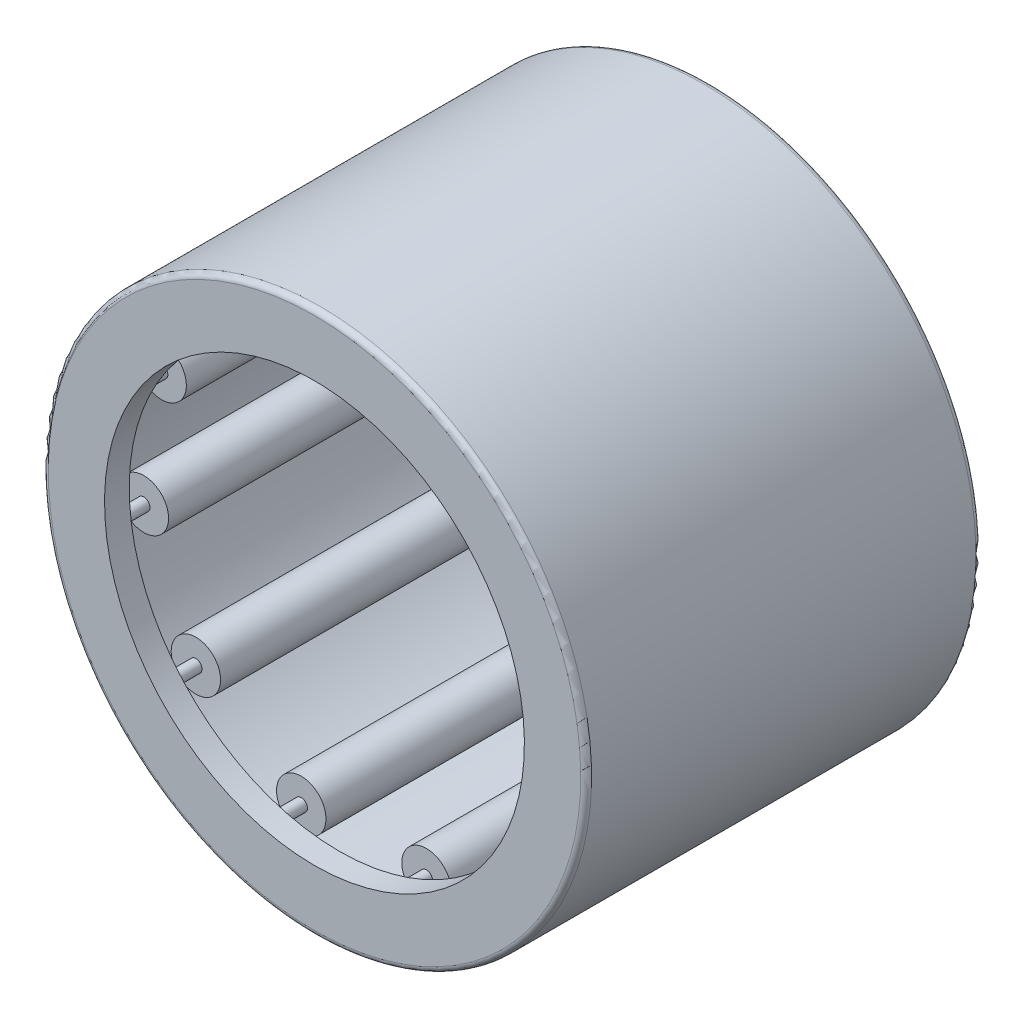
SolidWorks part; units mm, degrees
material "Plain Carbon Steel"
ref_plane "Front Plane" through (0, 0, 0) normal (0, 0, 1) x (1, 0, 0)
ref_plane "Top Plane" through (0, 0, 0) normal (0, 1, 0) x (1, 0, 0)
ref_plane "Right Plane" through (0, 0, 0) normal (1, 0, 0) x (0, 0, -1)
sketch "Sketch1" plane through (0, 0, 0) normal (1, 0, 0) x (0, 0, -1)
  line L0 (-6.35, 0) -> (6.35, 0) construction
  line L1 (0, 0) -> (0, 8.7313) construction
  line L2 (-6.35, 0) -> (-6.35, 8.7312) construction
  line L3 (-6.35, 8.7312) -> (6.35, 8.7312)
  line L4 (6.35, 8.7312) -> (6.35, 0) construction
  line L5 (6.35, 0) -> (5.5563, 0) construction
  line L6 (5.5563, 0) -> (5.5562, 7.9375) construction
  line L7 (5.5562, 7.9375) -> (-5.5562, 7.9375)
  line L8 (-5.5562, 7.9375) -> (-5.5563, 0) construction
  line L9 (-5.5563, 0) -> (-6.35, 0) construction
  line L10 (-6.35, 8.7312) -> (-6.35, 6.7469)
  line L11 (-6.35, 6.7469) -> (-5.5563, 6.7469)
  line L12 (-5.5563, 6.7469) -> (-5.5562, 7.9375)
  line L13 (5.5562, 8.7312) -> (5.5562, 7.9375) construction
  line L14 (5.5562, 7.9375) -> (5.5563, 6.7469)
  line L15 (5.5563, 6.7469) -> (6.35, 6.7469)
  line L16 (6.35, 6.7469) -> (6.35, 8.7312)
  line L17 (5.5562, 7.9375) -> (5.5563, 7.1437) construction
  line L18 (5.5563, 7.1437) -> (5.5562, 6.35) construction
  line L19 (5.5562, -7.9375) -> (5.5563, -7.1437) construction
  line L20 (5.5562, -8.7312) -> (5.5562, -7.9375) construction
  line L21 (6.35, -6.7469) -> (6.35, -8.7312) construction
  line L22 (5.5563, -6.7469) -> (6.35, -6.7469) construction
  line L23 (5.5562, -7.9375) -> (5.5563, -6.7469) construction
  line L24 (-5.5563, -6.7469) -> (-5.5562, -7.9375) construction
  line L25 (-6.35, -6.7469) -> (-5.5563, -6.7469) construction
  line L26 (-6.35, -8.7312) -> (-6.35, -6.7469) construction
  line L27 (5.5562, -7.9375) -> (-5.5562, -7.9375) construction
  line L28 (-6.35, -8.7312) -> (6.35, -8.7312) construction
  point P5 (0, 6.35)
  dimension "Width" = 12.7
  dimension "OD" = 17.4625
  dimension "Shaft Dia" = 12.7
revolve "Revolve1" add sketch "Sketch1" angle 360 about L0
sketch "Sketch2" plane through (0, 0, 0) normal (1, 0, 0) x (0, 0, -1)
  line L0 (5.5562, 7.9375) -> (-5.5562, 7.9375) construction
  line L1 (-4.7625, 7.1437) -> (4.7625, 7.1437) construction
  line L2 (-4.7625, 7.1437) -> (-4.7625, 7.9375) construction
  line L3 (-4.7625, 7.9375) -> (4.7625, 7.9375)
  line L4 (4.7625, 7.1437) -> (4.7625, 7.9375) construction
  line L5 (5.5563, 6.7469) -> (6.35, 6.7469) construction
  line L6 (-5.5563, 7.1437) -> (-4.7625, 7.1437) construction
  line L7 (4.7625, 7.1437) -> (5.5563, 7.1437) construction
  line L8 (-6.35, 6.7469) -> (-5.5563, 6.7469) construction
  line L9 (-4.7625, 7.3422) -> (-4.7625, 6.9453) construction
  line L10 (-5.5563, 7.1437) -> (-5.5563, 6.7469) construction
  line L11 (-4.7625, 7.9375) -> (-4.7625, 7.3422)
  line L12 (4.7625, 7.9375) -> (4.7625, 7.3422)
  line L13 (4.7625, 7.3422) -> (-4.7625, 7.3422)
  line L14 (0, 7.9375) -> (0, 6.35) construction
  line L15 (-5.5563, 6.7469) -> (-5.5563, 7.9375) construction
  line L16 (-4.7625, 6.9453) -> (-5.5563, 6.9453) construction
  line L17 (0, 0) -> (6.35, 0) construction
  line L18 (-4.7625, -6.9453) -> (-5.5563, -6.9453) construction
  line L19 (0, -7.9375) -> (0, -6.35) construction
  line L20 (-5.5563, -7.1437) -> (-5.5563, -6.7469) construction
  line L21 (-4.7625, -7.3422) -> (-4.7625, -6.9453) construction
  line L22 (4.7625, -7.1437) -> (5.5563, -7.1437) construction
  line L23 (-5.5563, -7.1437) -> (-4.7625, -7.1437) construction
  line L24 (4.7625, -7.1437) -> (4.7625, -7.9375) construction
  line L25 (-4.7625, -7.1437) -> (-4.7625, -7.9375) construction
  line L26 (-4.7625, -7.1437) -> (4.7625, -7.1437) construction
  line L27 (4.7625, -7.3422) -> (-4.7625, -7.3422) construction
  line L28 (4.7625, -7.9375) -> (4.7625, -7.3422) construction
  line L29 (-4.7625, -7.9375) -> (-4.7625, -7.3422) construction
  line L30 (-4.7625, -7.9375) -> (4.7625, -7.9375) construction
  line L31 (6.35, -8.7312) -> (6.35, 8.7312) construction
  point P16 (0, 7.1437)
revolve "Revolve2" add sketch "Sketch2" angle 360 about L1
sketch "Sketch3" plane through (0, 0, 0) normal (1, 0, 0) x (0, 0, -1)
  line L0 (5.5562, 7.9375) -> (5.5562, 6.7469) construction
  line L1 (-5.5563, 7.1437) -> (5.5562, 7.1437)
  line L2 (-5.5563, 7.1437) -> (-5.5563, 7.3422)
  line L3 (-5.5563, 7.3422) -> (5.5562, 7.3422)
  line L4 (5.5562, 7.1437) -> (5.5562, 7.3422)
  line L5 (0, 0) -> (6.35, 0) construction
  line L6 (6.35, -8.7312) -> (6.35, 8.7312) construction
  line L7 (5.5562, -7.1437) -> (5.5562, -7.3422) construction
  line L8 (-5.5563, -7.3422) -> (5.5562, -7.3422) construction
  line L9 (-5.5563, -7.1437) -> (-5.5563, -7.3422) construction
  line L10 (-5.5563, -7.1437) -> (5.5562, -7.1437) construction
revolve "Revolve3" add sketch "Sketch3" angle 360 about L1
sketch "Sketch6" plane through (0, 0, 0) normal (0, 0, 1) x (1, 0, 0)
  line L0 (0, 0) -> (4.4901, 5.5562) construction
  line L1 (0, 0) -> (0, 7.1437) construction
  line L2 (0, 7.1437) -> (4.4901, 5.5562) construction
  circle A0 centre (0, 7.1437) radius 0.7937 construction
  circle A1 centre (0, 7.1437) radius 0.7937
  circle A2 centre (0, 0) radius 7.1437 construction
  circle A3 centre (4.4901, 5.5562) radius 0.7937
  circle A4 centre (0, 0) radius 6.35 construction
  dimension "D1" = 1.5875
  dimension "D2" = 4.7625
ref_axis "Axis1" through (0, 0, -6.35) along (0, 0, 1)
pattern_circular "CirPattern1" count 11 every 32.727 about axis through (0, 0, -6.35) along (0, 0, 1) of bodies 166 167
fillet "Fillet1" radius 0.1746 2 edges at (0, -8.7312, -6.35) (0, -8.7312, 6.35)
sketch "Sketch4" plane through (0, 0, 0) normal (1, 0, 0) x (0, 0, -1)
  line L1 (6.1754, 6.35) -> (4.7625, 6.35)
  line L2 (6.1754, 6.35) -> (6.1754, 6.7469)
  line L3 (6.1754, 6.7469) -> (4.7625, 6.7469)
  line L4 (4.7625, 6.35) -> (4.7625, 6.7469)
  line L5 (-6.35, 6.7469) -> (-5.5563, 6.7469) construction
  line L6 (6.1754, -8.7312) -> (6.1754, 8.7312) construction
  line L7 (4.7625, 7.9375) -> (4.7625, 7.3422) construction
revolve "Revolve4" [suppressed] add sketch "Sketch4" angle 360 about L0
sketch "Sketch5" plane through (0, 0, 0) normal (1, 0, 0) x (0, 0, -1)
  line L0 (-6.1754, 8.7312) -> (-6.1754, -8.7312) construction
  line L1 (-4.7625, 6.35) -> (-6.1754, 6.35)
  line L2 (-4.7625, 6.35) -> (-4.7625, 6.7469)
  line L3 (-4.7625, 6.7469) -> (-6.1754, 6.7469)
  line L4 (-6.1754, 6.35) -> (-6.1754, 6.7469)
  line L6 (-4.7625, 7.9375) -> (-4.7625, 7.3422) construction
  line L7 (-6.35, 6.7469) -> (-5.5563, 6.7469) construction
revolve "Revolve5" [suppressed] add sketch "Sketch5" angle 360 about L0
equation "\"Rollers@CirPattern1\" = \"OD@Sketch1\"*16"
equation "\"D1@Fillet1\" = \"OD@Sketch1\"*.01"
equation "\"Angle@CirPattern1\"= 360 / \"Rollers@CirPattern1\""
